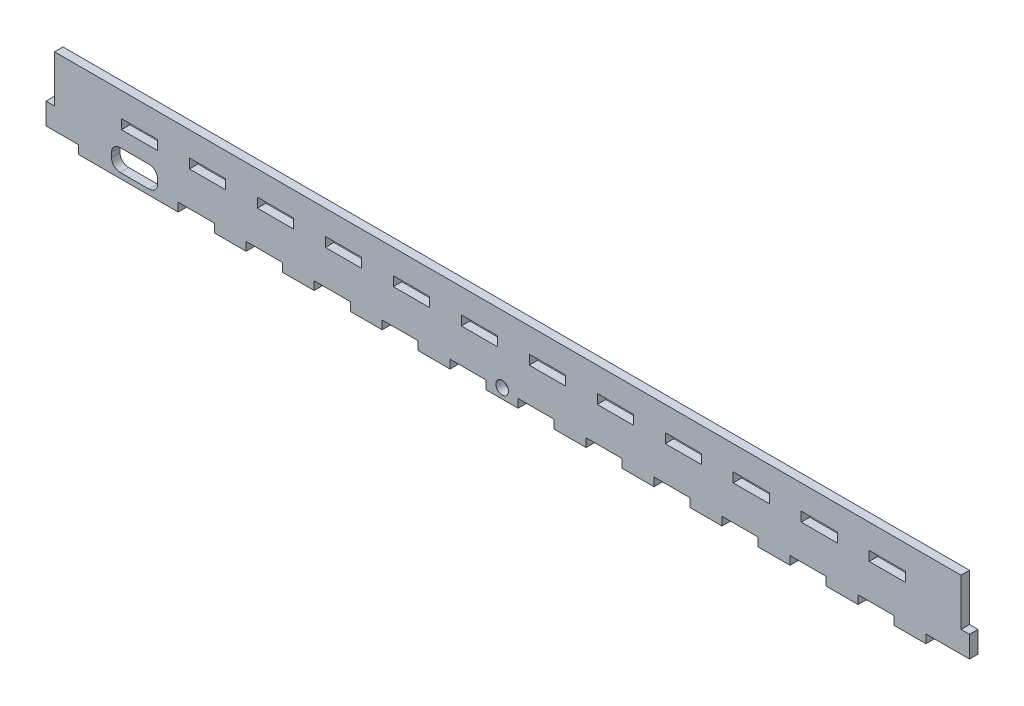
SolidWorks part; units mm, degrees
ref_plane "Plan de face" through (0, 0, 0) normal (0, 0, 1) x (1, 0, 0)
ref_plane "Plan de dessus" through (0, 0, 0) normal (0, 1, 0) x (1, 0, 0)
ref_plane "Plan de droite" through (0, 0, 0) normal (1, 0, 0) x (0, 0, -1)
sketch "Esquisse1" plane through (0, 0, 0) normal (0, 0, 1) x (1, 0, 0)
  line L1 (-108.68, -6.055) -> (108.68, -6.055)
  line L2 (-108.68, -6.055) -> (-108.68, 6.055)
  line L3 (-108.68, 6.055) -> (108.68, 6.055)
  line L4 (108.68, -6.055) -> (108.68, 6.055)
  line L5 (-108.68, -6.055) -> (108.68, 6.055) construction
  line L6 (-108.68, 6.055) -> (108.68, -6.055) construction
  point P0 (0, 0)
extrude "Boss.-Extru.1" add sketch "Esquisse1" along normal blind 2
sketch "Esquisse2" plane through (0, 0, 2) normal (0, 0, 1) x (1, 0, 0)
  line L0 (108.68, 6.055) -> (-108.68, 6.055) construction
  line L1 (-109.57, -4.055) -> (-108.68, -4.055)
  line L2 (-109.57, -4.055) -> (-109.57, -6.055)
  line L3 (-109.57, -6.055) -> (-101.07, -6.055)
  line L4 (-101.07, -4.055) -> (-101.07, -6.055)
  line L5 (-90.93, 4.055) -> (-82.43, 4.055)
  line L6 (-90.93, 4.055) -> (-90.93, 6.055)
  line L7 (-90.93, 6.055) -> (-82.43, 6.055)
  line L8 (-82.43, 4.055) -> (-82.43, 6.055)
  line L10 (-101.32, -6.055) -> (-108.68, -6.055) construction
  line L11 (-108.68, 6.055) -> (-108.68, -6.055) construction
  line L12 (-91.8767, 4.055) -> (-81.4833, 4.055) construction
  line L13 (-90.68, 6.055) -> (-82.68, 6.055) construction
  line L22 (-77.57, -4.055) -> (-69.07, -4.055)
  line L23 (-77.57, -4.055) -> (-77.57, -6.055)
  line L24 (-77.57, -6.055) -> (-69.07, -6.055)
  line L25 (-69.07, -4.055) -> (-69.07, -6.055)
  line L30 (-61.57, -4.055) -> (-53.07, -4.055)
  line L31 (-61.57, -4.055) -> (-61.57, -6.055)
  line L32 (-61.57, -6.055) -> (-53.07, -6.055)
  line L33 (-53.07, -4.055) -> (-53.07, -6.055)
  line L38 (-45.57, -4.055) -> (-37.07, -4.055)
  line L39 (-45.57, -4.055) -> (-45.57, -6.055)
  line L40 (-45.57, -6.055) -> (-37.07, -6.055)
  line L41 (-37.07, -4.055) -> (-37.07, -6.055)
  line L46 (-29.57, -4.055) -> (-21.07, -4.055)
  line L47 (-29.57, -4.055) -> (-29.57, -6.055)
  line L48 (-29.57, -6.055) -> (-21.07, -6.055)
  line L49 (-21.07, -4.055) -> (-21.07, -6.055)
  line L54 (-13.57, -4.055) -> (-5.07, -4.055)
  line L55 (-13.57, -4.055) -> (-13.57, -6.055)
  line L56 (-13.57, -6.055) -> (-5.07, -6.055)
  line L57 (-5.07, -4.055) -> (-5.07, -6.055)
  line L62 (2.43, -4.055) -> (10.93, -4.055)
  line L63 (2.43, -4.055) -> (2.43, -6.055)
  line L64 (2.43, -6.055) -> (10.93, -6.055)
  line L65 (10.93, -4.055) -> (10.93, -6.055)
  line L70 (18.43, -4.055) -> (26.93, -4.055)
  line L71 (18.43, -4.055) -> (18.43, -6.055)
  line L72 (18.43, -6.055) -> (26.93, -6.055)
  line L73 (26.93, -4.055) -> (26.93, -6.055)
  line L78 (34.43, -4.055) -> (42.93, -4.055)
  line L79 (34.43, -4.055) -> (34.43, -6.055)
  line L80 (34.43, -6.055) -> (42.93, -6.055)
  line L81 (42.93, -4.055) -> (42.93, -6.055)
  line L86 (50.43, -4.055) -> (58.93, -4.055)
  line L87 (50.43, -4.055) -> (50.43, -6.055)
  line L88 (50.43, -6.055) -> (58.93, -6.055)
  line L89 (58.93, -4.055) -> (58.93, -6.055)
  line L94 (66.43, -4.055) -> (74.93, -4.055)
  line L95 (66.43, -4.055) -> (66.43, -6.055)
  line L96 (66.43, -6.055) -> (74.93, -6.055)
  line L97 (74.93, -4.055) -> (74.93, -6.055)
  line L102 (82.43, -4.055) -> (90.93, -4.055)
  line L103 (82.43, -4.055) -> (82.43, -6.055)
  line L104 (82.43, -6.055) -> (90.93, -6.055)
  line L105 (90.93, -4.055) -> (90.93, -6.055)
  line L110 (101.07, 4.055) -> (109.57, 4.055) [skipped]
  line L111 (101.07, 4.055) -> (101.07, 6.055) [skipped]
  line L112 (101.07, 6.055) -> (109.57, 6.055) [skipped]
  line L113 (109.57, 4.055) -> (109.57, 6.055) [skipped]
  line L114 (-77.32, -6.055) -> (-77.32, -4.055) construction
  line L115 (-69.32, -4.055) -> (-69.32, -6.055) construction
  line L117 (-74.93, 4.055) -> (-66.43, 4.055) [skipped]
  line L118 (-74.93, 4.055) -> (-74.93, 6.055) [skipped]
  line L119 (-74.93, 6.055) -> (-66.43, 6.055) [skipped]
  line L120 (-66.43, 4.055) -> (-66.43, 6.055) [skipped]
  line L121 (-58.93, 4.055) -> (-50.43, 4.055) [skipped]
  line L122 (-58.93, 4.055) -> (-58.93, 6.055) [skipped]
  line L123 (-58.93, 6.055) -> (-50.43, 6.055) [skipped]
  line L124 (-50.43, 4.055) -> (-50.43, 6.055) [skipped]
  line L125 (-42.93, 4.055) -> (-34.43, 4.055) [skipped]
  line L126 (-42.93, 4.055) -> (-42.93, 6.055) [skipped]
  line L127 (-42.93, 6.055) -> (-34.43, 6.055) [skipped]
  line L128 (-34.43, 4.055) -> (-34.43, 6.055) [skipped]
  line L129 (-26.93, 4.055) -> (-18.43, 4.055) [skipped]
  line L130 (-26.93, 4.055) -> (-26.93, 6.055) [skipped]
  line L131 (-26.93, 6.055) -> (-18.43, 6.055) [skipped]
  line L132 (-18.43, 4.055) -> (-18.43, 6.055) [skipped]
  line L133 (-10.93, 4.055) -> (-2.43, 4.055) [skipped]
  line L134 (-10.93, 4.055) -> (-10.93, 6.055) [skipped]
  line L135 (-10.93, 6.055) -> (-2.43, 6.055) [skipped]
  line L136 (-2.43, 4.055) -> (-2.43, 6.055) [skipped]
  line L137 (5.07, 4.055) -> (13.57, 4.055) [skipped]
  line L138 (5.07, 4.055) -> (5.07, 6.055) [skipped]
  line L139 (5.07, 6.055) -> (13.57, 6.055) [skipped]
  line L140 (13.57, 4.055) -> (13.57, 6.055) [skipped]
  line L141 (21.07, 4.055) -> (29.57, 4.055) [skipped]
  line L142 (21.07, 4.055) -> (21.07, 6.055) [skipped]
  line L143 (21.07, 6.055) -> (29.57, 6.055) [skipped]
  line L144 (29.57, 4.055) -> (29.57, 6.055) [skipped]
  line L145 (37.07, 4.055) -> (45.57, 4.055) [skipped]
  line L146 (37.07, 4.055) -> (37.07, 6.055) [skipped]
  line L147 (37.07, 6.055) -> (45.57, 6.055) [skipped]
  line L148 (45.57, 4.055) -> (45.57, 6.055) [skipped]
  line L149 (53.07, 4.055) -> (61.57, 4.055) [skipped]
  line L150 (53.07, 4.055) -> (53.07, 6.055) [skipped]
  line L151 (53.07, 6.055) -> (61.57, 6.055) [skipped]
  line L152 (61.57, 4.055) -> (61.57, 6.055) [skipped]
  line L153 (69.07, 4.055) -> (77.57, 4.055) [skipped]
  line L154 (69.07, 4.055) -> (69.07, 6.055) [skipped]
  line L155 (69.07, 6.055) -> (77.57, 6.055) [skipped]
  line L156 (77.57, 4.055) -> (77.57, 6.055) [skipped]
  line L157 (85.07, 4.055) -> (93.57, 4.055) [skipped]
  line L158 (85.07, 4.055) -> (85.07, 6.055) [skipped]
  line L159 (85.07, 6.055) -> (93.57, 6.055) [skipped]
  line L160 (93.57, 4.055) -> (93.57, 6.055) [skipped]
  line L161 (-82.68, 4.055) -> (-82.68, 6.055) construction
  line L162 (-74.93, 4.055) -> (-66.43, 4.055)
  line L163 (-74.93, 4.055) -> (-74.93, 6.055)
  line L164 (-74.93, 6.055) -> (-66.43, 6.055)
  line L165 (-66.43, 4.055) -> (-66.43, 6.055)
  line L166 (-58.93, 4.055) -> (-50.43, 4.055)
  line L167 (-58.93, 4.055) -> (-58.93, 6.055)
  line L168 (-58.93, 6.055) -> (-50.43, 6.055)
  line L169 (-50.43, 4.055) -> (-50.43, 6.055)
  line L170 (-42.93, 4.055) -> (-34.43, 4.055)
  line L171 (-42.93, 4.055) -> (-42.93, 6.055)
  line L172 (-42.93, 6.055) -> (-34.43, 6.055)
  line L173 (-34.43, 4.055) -> (-34.43, 6.055)
  line L174 (-26.93, 4.055) -> (-18.43, 4.055)
  line L175 (-26.93, 4.055) -> (-26.93, 6.055)
  line L176 (-26.93, 6.055) -> (-18.43, 6.055)
  line L177 (-18.43, 4.055) -> (-18.43, 6.055)
  line L178 (-10.93, 4.055) -> (-2.43, 4.055)
  line L179 (-10.93, 4.055) -> (-10.93, 6.055)
  line L180 (-10.93, 6.055) -> (-2.43, 6.055)
  line L181 (-2.43, 4.055) -> (-2.43, 6.055)
  line L182 (5.07, 4.055) -> (13.57, 4.055)
  line L183 (5.07, 4.055) -> (5.07, 6.055)
  line L184 (5.07, 6.055) -> (13.57, 6.055)
  line L185 (13.57, 4.055) -> (13.57, 6.055)
  line L186 (21.07, 4.055) -> (29.57, 4.055)
  line L187 (21.07, 4.055) -> (21.07, 6.055)
  line L188 (21.07, 6.055) -> (29.57, 6.055)
  line L189 (29.57, 4.055) -> (29.57, 6.055)
  line L190 (37.07, 4.055) -> (45.57, 4.055)
  line L191 (37.07, 4.055) -> (37.07, 6.055)
  line L192 (37.07, 6.055) -> (45.57, 6.055)
  line L193 (45.57, 4.055) -> (45.57, 6.055)
  line L194 (53.07, 4.055) -> (61.57, 4.055)
  line L195 (53.07, 4.055) -> (53.07, 6.055)
  line L196 (53.07, 6.055) -> (61.57, 6.055)
  line L197 (61.57, 4.055) -> (61.57, 6.055)
  line L198 (69.07, 4.055) -> (77.57, 4.055)
  line L199 (69.07, 4.055) -> (69.07, 6.055)
  line L200 (69.07, 6.055) -> (77.57, 6.055)
  line L201 (77.57, 4.055) -> (77.57, 6.055)
  line L202 (85.07, 4.055) -> (93.57, 4.055)
  line L203 (85.07, 4.055) -> (85.07, 6.055)
  line L204 (85.07, 6.055) -> (93.57, 6.055)
  line L205 (93.57, 4.055) -> (93.57, 6.055)
  line L206 (93.32, 4.055) -> (93.32, 6.055) construction
  line L207 (90.68, -4.055) -> (90.68, -6.055) construction
  line L208 (82.68, -4.055) -> (90.68, -4.055) construction
  line L209 (-108.68, -6.055) -> (108.68, -6.055) construction
  line L210 (98.43, -6.055) -> (108.68, -6.055)
  line L211 (98.43, -6.055) -> (98.43, -4.055)
  line L212 (98.43, -4.055) -> (108.68, -4.055)
  line L213 (108.68, -6.055) -> (108.68, -4.055)
  line L214 (108.68, -6.055) -> (108.68, 6.055) construction
  line L215 (108.68, -4.305) -> (98.68, -4.305) construction
  line L216 (98.68, -6.055) -> (98.68, -4.055) construction
  line L220 (-108.68, -4.055) -> (-101.07, -4.055)
  line L223 (-108.68, -4.055) -> (-101.07, -4.055) construction
  line L224 (-93.57, -4.055) -> (-85.07, -4.055) [skipped]
  line L225 (-93.57, -4.055) -> (-93.57, -6.055) [skipped]
  line L226 (-93.57, -6.055) -> (-85.07, -6.055) [skipped]
  line L227 (-85.07, -4.055) -> (-85.07, -6.055) [skipped]
  point P3 (-89, -4.055)
  point P8 (0, 0)
  point P9 (0, 0)
  point P11 (0, 0)
  point P12 (0, 0)
  point P17 (-86.68, 4.055)
  point P21 (0, 0)
  point P24 (105.32, 4.055)
  point P27 (0, 0)
  point P28 (89.32, 4.055)
  point P29 (73.32, 4.055)
  point P30 (57.32, 4.055)
  point P31 (41.32, 4.055)
  point P38 (25.32, 4.055)
  point P39 (9.32, 4.055)
  point P40 (-6.68, 4.055)
  point P41 (-22.68, 4.055)
  point P42 (0, 0)
  point P43 (-70.68, 4.055)
  point P48 (-38.68, 4.055)
  point P49 (-54.68, 4.055)
  point P52 (0, 0)
  point P58 (-70.68, 4.055)
  point P62 (0, 0)
  point P68 (-54.68, 4.055)
  point P72 (0, 0)
  point P78 (-38.68, 4.055)
  point P82 (0, 0)
  point P88 (-22.68, 4.055)
  point P92 (0, 0)
  point P98 (-6.68, 4.055)
  point P108 (9.32, 4.055)
  point P112 (0, 0)
  point P118 (25.32, 4.055)
  point P122 (0, 0)
  point P128 (41.32, 4.055)
  point P141 (57.32, 4.055)
  point P243 (73.32, 4.055)
  point P248 (89.32, 4.055)
  point P267 (0, 0)
  point P272 (-61.6433, 4.055)
  point P273 (0, 0)
  point P282 (-101.28, -3.725)
  dimension "D1" = 0.25
  dimension "D2" = 0.25
  dimension "D4" = 0.25
  dimension "D6" = 0.25
  dimension "D7" = 0.25
  dimension "D8" = 0.25
  dimension "D9" = 0.25
  dimension "D11" = 7.5
  dimension "D12" = 8.5
  dimension "D13" = 10.25
  dimension "D14" = 7.5
  dimension "D15" = 17.75
  dimension "D16" = 7.5
  dimension "D3" = 13
  dimension "D5" = 12
extrude "Enlèv. mat.-Extru.1" cut sketch "Esquisse2" against normal through all
sketch "Esquisse3" plane through (0, 0, 2) normal (0, 0, 1) x (1, 0, 0)
  line L0 (-93.002, -1.925) -> (-93.002, -2.625) construction
  line L1 (-91.252, 0.255) -> (-84.412, 0.255)
  line L2 (-93.252, -1.745) -> (-93.252, -2.805)
  line L3 (-91.252, -4.805) -> (-84.412, -4.805)
  line L4 (-82.412, -1.745) -> (-82.412, -2.805)
  line L5 (-82.662, -2.625) -> (-82.662, -1.925) construction
  line L6 (-84.592, 0.005) -> (-91.072, 0.005) construction
  line L7 (-91.072, -4.555) -> (-84.592, -4.555) construction
  arc A0 (-93.252, -2.805) -> (-91.252, -4.805) centre (-91.252, -2.805) ccw
  arc A1 (-84.412, 0.255) -> (-82.412, -1.745) centre (-84.412, -1.745) cw
  arc A2 (-84.412, -4.805) -> (-82.412, -2.805) centre (-84.412, -2.805) ccw
  arc A3 (-91.252, 0.255) -> (-93.252, -1.745) centre (-91.252, -1.745) ccw
  dimension "D5" = 2
  dimension "D1" = 0.25
  dimension "D2" = 0.25
  dimension "D3" = 0.25
  dimension "D4" = 0.25
extrude "Enlèv. mat.-Extru.2" cut sketch "Esquisse3" against normal through all
sketch "Esquisse5" plane through (0, 0, 2) normal (0, 0, 1) x (1, 0, 0)
  line L0 (0, 0) -> (0, -11.5957) construction
  line L1 (-108.68, 1) -> (-106.68, 1)
  line L2 (-108.68, 1) -> (-108.68, 6.055)
  line L3 (-108.68, 6.055) -> (-106.68, 6.055)
  line L4 (-106.68, 1) -> (-106.68, 6.055)
  line L5 (106.68, 1) -> (106.68, 6.055)
  line L6 (108.68, 6.055) -> (106.68, 6.055)
  line L7 (108.68, 1) -> (108.68, 6.055)
  line L8 (108.68, 1) -> (106.68, 1)
extrude "Enlèv. mat.-Extru.3" cut sketch "Esquisse5" against normal through all
sketch "Esquisse6" plane through (0, 0, 2) normal (0, 0, 1) x (1, 0, 0)
  line L1 (-106.68, 6.055) -> (106.68, 6.055)
  line L2 (-106.68, 6.055) -> (-106.68, 12.055)
  line L3 (-106.68, 12.055) -> (106.68, 12.055)
  line L4 (106.68, 6.055) -> (106.68, 12.055)
extrude "Boss.-Extru.2" add sketch "Esquisse6" against normal up to surface (2 mm away) up to face at (3.3846, 0.0769, 0)
sketch "Esquisse7" plane through (0, 0, 2) normal (0, 0, 1) x (1, 0, 0)
  line L0 (-74.93, 6.055) -> (-66.43, 6.055)
  line L1 (-90.93, 6.055) -> (-82.43, 6.055)
  line L2 (-90.93, 6.055) -> (-90.93, 6.305)
  line L3 (-90.93, 6.305) -> (-82.43, 6.305)
  line L4 (-82.43, 6.055) -> (-82.43, 6.305)
  line L5 (-74.93, 6.055) -> (-74.93, 6.305)
  line L6 (-74.93, 6.305) -> (-66.43, 6.305)
  line L7 (-66.43, 6.055) -> (-66.43, 6.305)
  line L8 (-58.93, 6.055) -> (-50.43, 6.055)
  line L9 (-58.93, 6.055) -> (-58.93, 6.305)
  line L10 (-58.93, 6.305) -> (-50.43, 6.305)
  line L11 (-50.43, 6.055) -> (-50.43, 6.305)
  line L12 (-42.93, 6.055) -> (-34.43, 6.055)
  line L13 (-42.93, 6.055) -> (-42.93, 6.305)
  line L14 (-42.93, 6.305) -> (-34.43, 6.305)
  line L15 (-34.43, 6.055) -> (-34.43, 6.305)
  line L16 (-26.93, 6.055) -> (-18.43, 6.055)
  line L17 (-26.93, 6.055) -> (-26.93, 6.305)
  line L18 (-26.93, 6.305) -> (-18.43, 6.305)
  line L19 (-18.43, 6.055) -> (-18.43, 6.305)
  line L20 (-10.93, 6.055) -> (-2.43, 6.055)
  line L21 (-10.93, 6.055) -> (-10.93, 6.305)
  line L22 (-10.93, 6.305) -> (-2.43, 6.305)
  line L23 (-2.43, 6.055) -> (-2.43, 6.305)
  line L24 (5.07, 6.055) -> (13.57, 6.055)
  line L25 (5.07, 6.055) -> (5.07, 6.305)
  line L26 (5.07, 6.305) -> (13.57, 6.305)
  line L27 (13.57, 6.055) -> (13.57, 6.305)
  line L28 (21.07, 6.055) -> (29.57, 6.055)
  line L29 (21.07, 6.055) -> (21.07, 6.305)
  line L30 (21.07, 6.305) -> (29.57, 6.305)
  line L31 (29.57, 6.055) -> (29.57, 6.305)
  line L32 (37.07, 6.055) -> (45.57, 6.055)
  line L33 (37.07, 6.055) -> (37.07, 6.305)
  line L34 (37.07, 6.305) -> (45.57, 6.305)
  line L35 (45.57, 6.055) -> (45.57, 6.305)
  line L36 (53.07, 6.055) -> (61.57, 6.055)
  line L37 (53.07, 6.055) -> (53.07, 6.305)
  line L38 (53.07, 6.305) -> (61.57, 6.305)
  line L39 (61.57, 6.055) -> (61.57, 6.305)
  line L40 (69.07, 6.055) -> (77.57, 6.055)
  line L41 (69.07, 6.055) -> (69.07, 6.305)
  line L42 (69.07, 6.305) -> (77.57, 6.305)
  line L43 (77.57, 6.055) -> (77.57, 6.305)
  line L44 (85.07, 6.055) -> (93.57, 6.055)
  line L45 (85.07, 6.055) -> (85.07, 6.305)
  line L46 (85.07, 6.305) -> (93.57, 6.305)
  line L47 (93.57, 6.055) -> (93.57, 6.305)
  line L48 (85.07, 6.055) -> (93.57, 6.055) construction
  dimension "D1" = 0.25
  dimension "D2" = 12
extrude "Enlèv. mat.-Extru.4" cut sketch "Esquisse7" against normal through all
sketch "Sketch1" plane through (0, 0, 2) normal (0, 0, 1) x (1, 0, 0)
  circle A0 centre (-1.32, -3.725) radius 1.5
  dimension "D1" = 3
extrude "Cut-Extrude1" cut sketch "Sketch1" against normal through all
